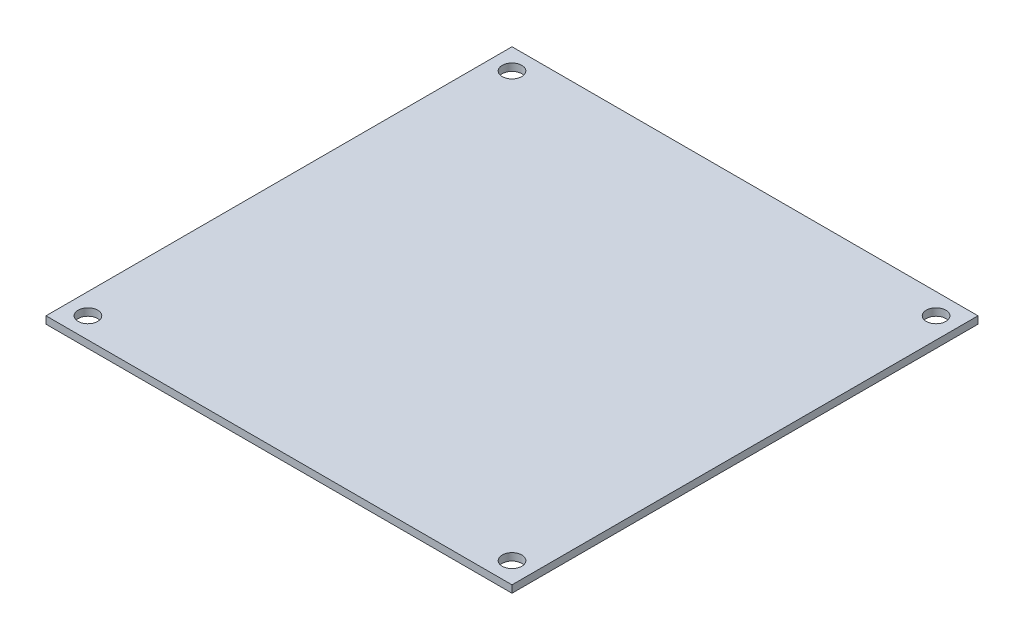
SolidWorks part; units mm, degrees
ref_plane "Front" through (0, 0, 0) normal (0, 0, 1) x (1, 0, 0)
ref_plane "Top" through (0, 0, 0) normal (0, 1, 0) x (1, 0, 0)
ref_plane "Right" through (0, 0, 0) normal (1, 0, 0) x (0, 0, -1)
sketch "Sketch1" plane through (0, 0, 0) normal (0, 1, 0) x (1, 0, 0)
  line L0 (0, 100) -> (100, 0) construction
  line L1 (0, 0) -> (100, 0)
  line L2 (0, 0) -> (0, 100)
  line L3 (0, 100) -> (100, 100)
  line L4 (100, 0) -> (100, 100)
  line L5 (100, 100) -> (0, 0) construction
  line L7 (4.5, 4.5) -> (95.5, 4.5) construction
  line L8 (4.5, 4.5) -> (4.5, 95.5) construction
  line L9 (4.5, 95.5) -> (95.5, 95.5) construction
  line L10 (95.5, 4.5) -> (95.5, 95.5) construction
  line L11 (4.5, 4.5) -> (95.5, 95.5) construction
  line L12 (4.5, 95.5) -> (95.5, 4.5) construction
  circle A1 centre (4.5, 95.5) radius 2.1
  circle A2 centre (95.5, 95.5) radius 2.1
  circle A3 centre (95.5, 4.5) radius 2.1
  circle A4 centre (4.5, 4.5) radius 2.1
  point P4 (50, 50)
  dimension "D3" = 91
  dimension "D6" = 4.2
  dimension "D1" = 100
  dimension "D2" = 100
  dimension "D4" = 91
extrude "Boss-Extrude1" add sketch "Sketch1" along normal blind 1.57
